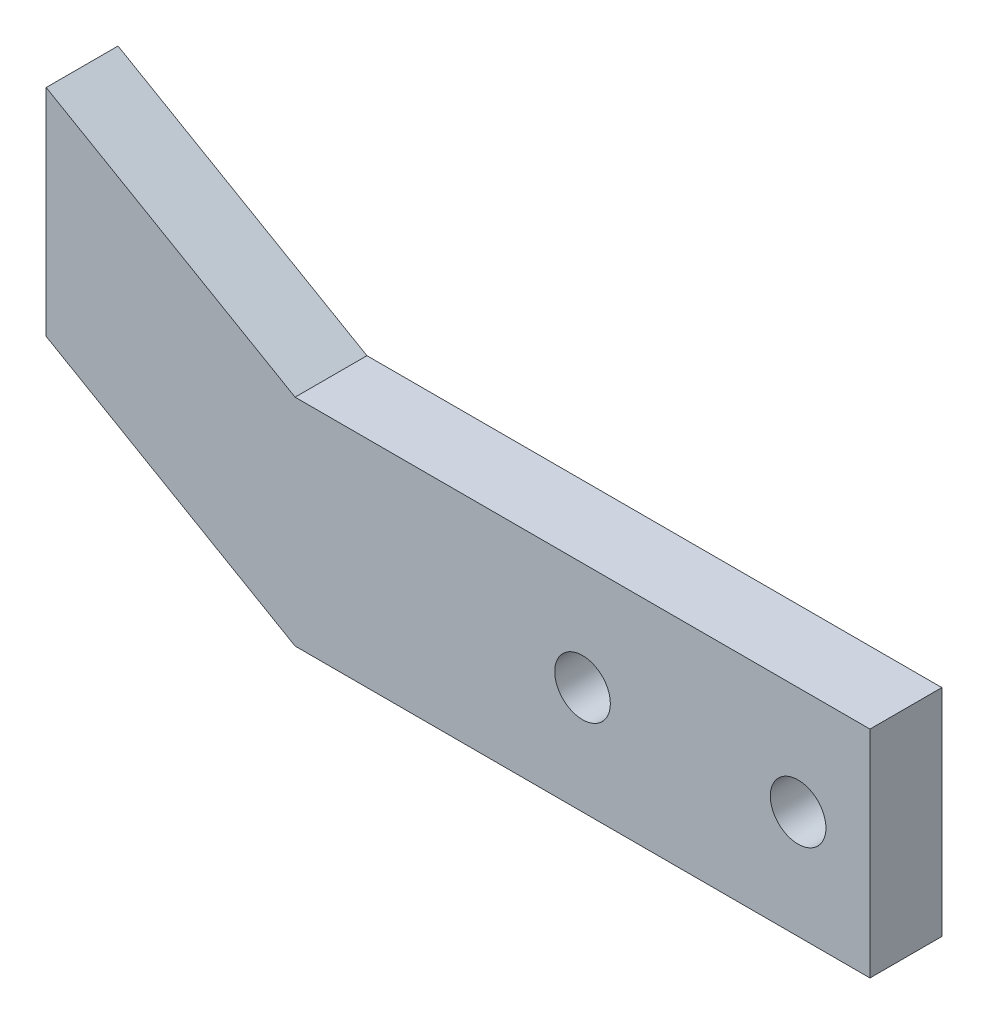
SolidWorks part; units mm, degrees
ref_plane "Front Plane" through (0, 0, 0) normal (0, 0, 1) x (1, 0, 0)
ref_plane "Top Plane" through (0, 0, 0) normal (0, 1, 0) x (1, 0, 0)
ref_plane "Right Plane" through (0, 0, 0) normal (1, 0, 0) x (0, 0, -1)
sketch "Sketch1" plane through (0, 0, 0) normal (0, 0, 1) x (1, 0, 0)
  line L0 (0, 0) -> (-21.997, 12.7)
  line L1 (0, 0) -> (50.8, 0)
  line L3 (0, 19.05) -> (50.8, 19.05)
  line L4 (50.8, 0) -> (50.8, 19.05)
  line L5 (-21.997, 12.7) -> (-21.997, 31.75)
  line L6 (-21.997, 31.75) -> (0, 19.05)
  dimension "D1" = 19.05
  dimension "D2" = 150
  dimension "D3" = 25.4
  dimension "D4" = 50.8
  dimension "D5" = 50.8
extrude "Boss-Extrude1" add sketch "Sketch1" along normal blind 6.35
hole_wizard "#10 (0.1935) Diameter Hole1" positions "Sketch3" profile "Sketch2" hole size "#10" standard "ANSI Inch" end condition through all
sketch "Sketch3" plane through (0, 0, 6.35) normal (0, 0, 1) x (1, 0, 0)
  line L0 (50.8, 9.525) -> (-16.4978, 9.525) construction
  line L1 (50.8, 0) -> (50.8, 19.05) construction
  line L2 (-21.997, 12.7) -> (0, 0) construction
  point P0 (44.45, 9.525)
  point P2 (25.4, 9.525)
  dimension "D1" = 6.35
  dimension "D2" = 19.05
sketch "Sketch2" plane through (44.45, 9.525, 6.35) normal (1, 0, 0) x (0, -1, 0)
  line L0 (0, 0) -> (0, 6.35)
  line L1 (0, 6.35) -> (2.4574, 6.35)
  line L2 (2.4574, 6.35) -> (2.4574, 0)
  line L5 (2.4574, 0) -> (0, 0)
  line L11 (0, -6.35) -> (0, 107.95) construction
  dimension "Thru Hole Dia." = 4.9149
  dimension "Thru Hole Depth" = 6.35
